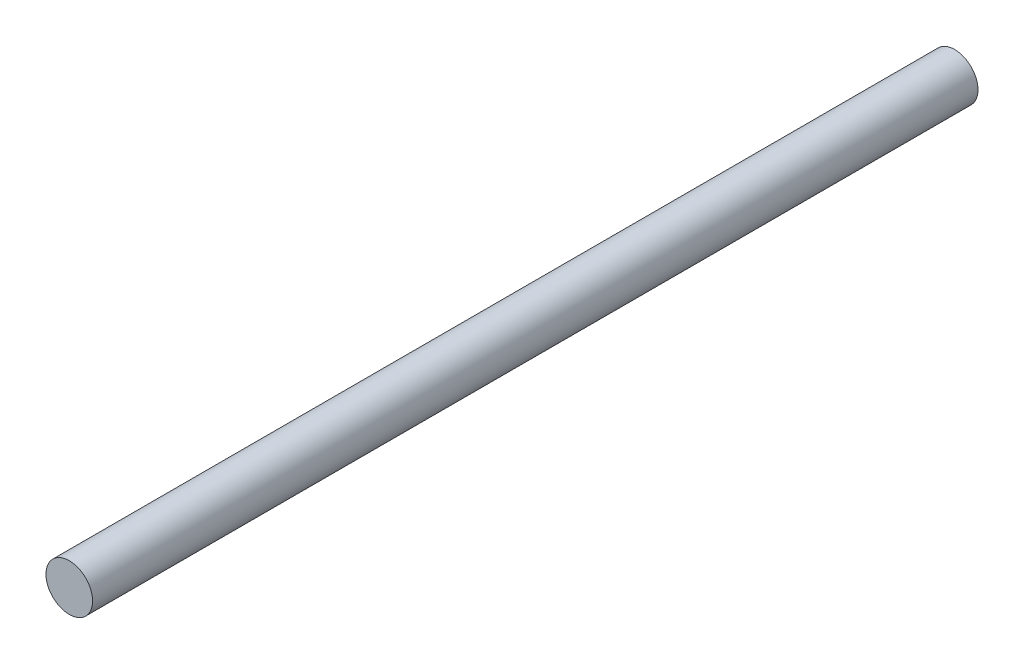
SolidWorks part; units mm, degrees
ref_plane "Front Plane" through (0, 0, 0) normal (0, 0, 1) x (1, 0, 0)
ref_plane "Top Plane" through (0, 0, 0) normal (0, 1, 0) x (1, 0, 0)
ref_plane "Right Plane" through (0, 0, 0) normal (1, 0, 0) x (0, 0, -1)
sketch "Sketch1" plane through (0, 0, 0) normal (0, 0, 1) x (1, 0, 0)
  circle A0 centre (0, 0) radius 5
  dimension "D1" = 10
extrude "Boss-Extrude1" add sketch "Sketch1" along normal blind 190
